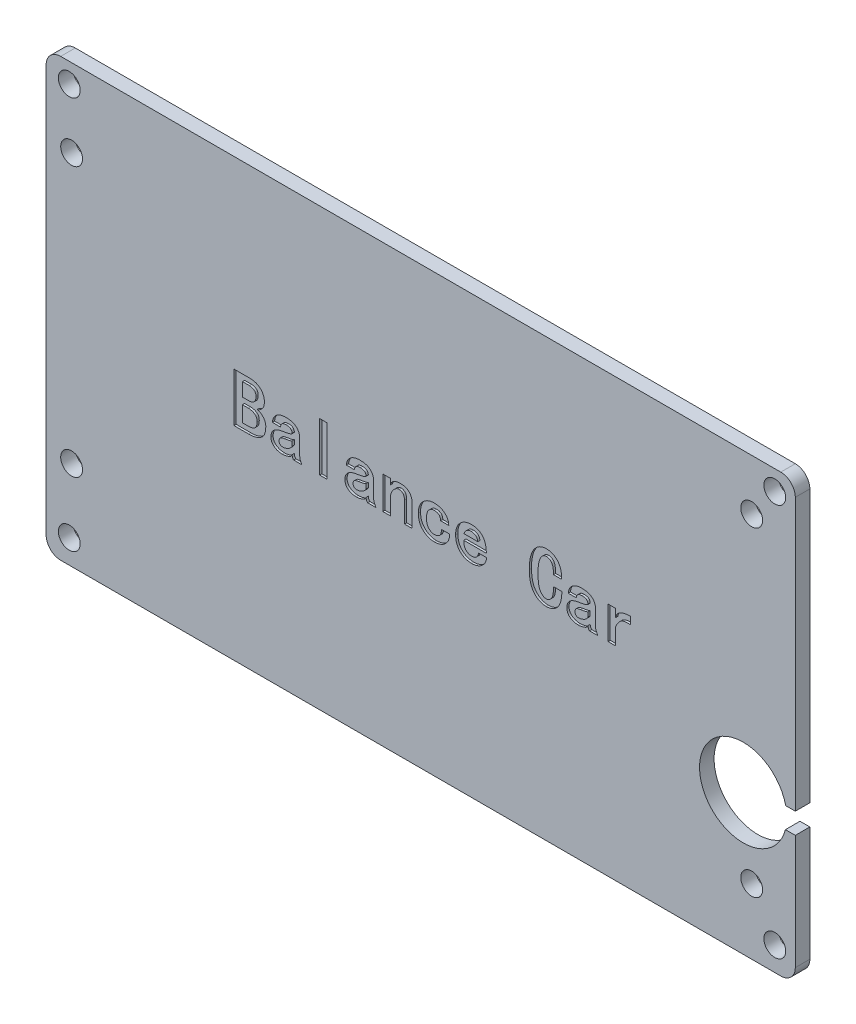
SolidWorks part; units mm, degrees
ref_plane "前视基准面" through (0, 0, 0) normal (0, 0, 1) x (1, 0, 0)
ref_plane "上视基准面" through (0, 0, 0) normal (0, 1, 0) x (1, 0, 0)
ref_plane "右视基准面" through (0, 0, 0) normal (1, 0, 0) x (0, 0, -1)
sketch "草图1" plane through (0, 0, 0) normal (0, 0, 1) x (1, 0, 0)
  line L0 (26.8171, -30.979) -> (26.8171, -46.7301)
  line L1 (-74.1829, 11.2699) -> (24.8171, 11.2699)
  line L2 (-76.1829, 9.2699) -> (-76.1829, -46.7301)
  line L3 (-74.1829, -48.7301) -> (24.8171, -48.7301)
  line L4 (26.8171, 9.2699) -> (26.8171, -28.1061)
  line L5 (25.4979, -28.1061) -> (26.8171, -28.1061)
  line L7 (25.4583, -30.979) -> (26.8171, -30.979)
  line L10 (-76.1829, -18.7301) -> (26.8171, -18.7301) construction
  circle A0 centre (-73.0047, 8.5605) radius 1.5
  circle A1 centre (23.9953, 8.5605) radius 1.5
  circle A2 centre (20.8171, 4.2699) radius 1.5
  arc A3 (25.4979, -28.1061) -> (25.4583, -30.979) centre (19.6531, -29.4622) ccw
  circle A4 centre (-72.6829, 0.5476) radius 1.5
  circle A5 centre (-73.0047, -45.4395) radius 1.5
  circle A6 centre (-72.6829, -36.4524) radius 1.5
  circle A11 centre (23.9953, -45.4395) radius 1.5
  circle A12 centre (20.8171, -39.7301) radius 1.5
  arc A20 (-74.1829, 11.2699) -> (-76.1829, 9.2699) centre (-74.1829, 9.2699) ccw
  arc A21 (-74.1829, -48.7301) -> (-76.1829, -46.7301) centre (-74.1829, -46.7301) cw
  arc A22 (24.8171, -48.7301) -> (26.8171, -46.7301) centre (24.8171, -46.7301) ccw
  arc A23 (26.8171, 9.2699) -> (24.8171, 11.2699) centre (24.8171, 9.2699) ccw
  point P22 (25.4959, -28.1061)
  point P23 (26.8171, -28.1061)
  point P24 (26.8171, -30.979)
  point P30 (25.4583, -30.979)
  point P50 (8.726, -18.7301)
  point P56 (-76.1829, 11.2699)
  point P61 (26.8171, -48.7301)
  point P64 (26.8171, 11.2699)
  dimension "D1" = 3
  dimension "D19" = 2
  dimension "D9" = 12
  dimension "D2" = 97
  dimension "D3" = 37
  dimension "D4" = 54
  dimension "D5" = 60
  dimension "D6" = 44
  dimension "D7" = 6
  dimension "D8" = 7
  dimension "D13" = 103
  dimension "D16" = 3.5
extrude "凸台-拉伸1" add sketch "草图1" along normal blind 2
sketch "草图2" plane through (0, 0, 2) normal (0, 0, 1) x (1, 0, 0)
  text T0 "<b>Balance Car</b>" font "黑体" height in points 22
extrude "切除-拉伸1" cut sketch "草图2" against normal blind 0.3
